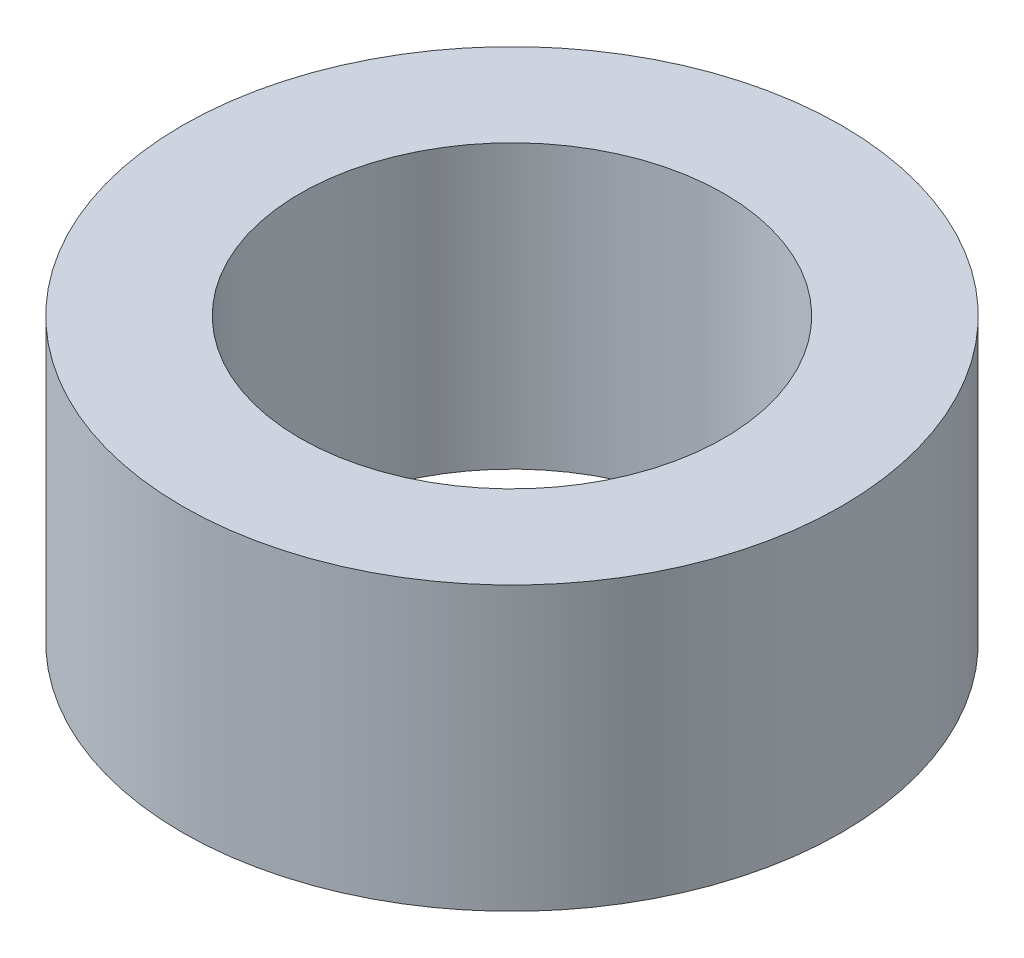
SolidWorks part; units mm, degrees
ref_plane "前视基准面" through (0, 0, 0) normal (0, 0, 1) x (1, 0, 0)
ref_plane "上视基准面" through (0, 0, 0) normal (0, 1, 0) x (1, 0, 0)
ref_plane "右视基准面" through (0, 0, 0) normal (1, 0, 0) x (0, 0, -1)
other "Configuration Table"
sketch "草图1" plane through (0, 0, 0) normal (0, 1, 0) x (1, 0, 0)
  circle A0 centre (0, 0) radius 2.25
  circle A1 centre (0, 0) radius 3.5
  dimension "D1" = 4.5
  dimension "D2" = 7
extrude "凸台-拉伸1" add sketch "草图1" along normal blind 3
